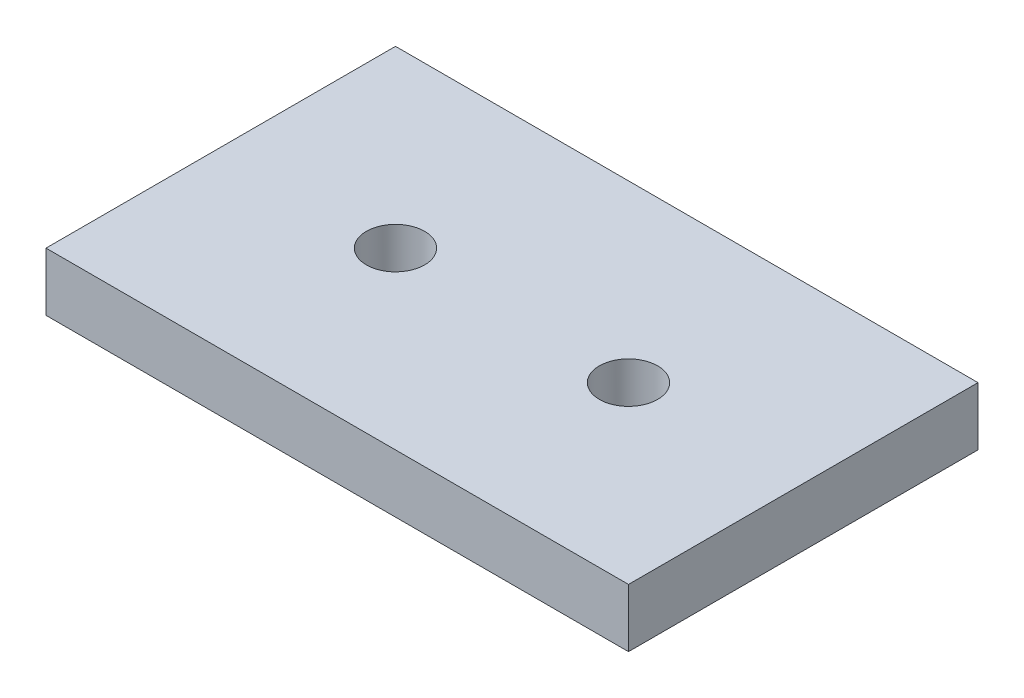
SolidWorks part; units mm, degrees
ref_plane "前视基准面" through (0, 0, 0) normal (0, 0, 1) x (1, 0, 0)
ref_plane "上视基准面" through (0, 0, 0) normal (0, 1, 0) x (1, 0, 0)
ref_plane "右视基准面" through (0, 0, 0) normal (1, 0, 0) x (0, 0, -1)
other "Configuration Table"
sketch "草图1" plane through (0, 0, 0) normal (0, 1, 0) x (1, 0, 0)
  line L1 (-50, -30) -> (50, -30)
  line L2 (-50, -30) -> (-50, 30)
  line L3 (-50, 30) -> (50, 30)
  line L4 (50, -30) -> (50, 30)
  line L5 (0, 30) -> (0, -30) construction
  line L6 (-50, 0) -> (50, 0) construction
  point P0 (0, 0)
extrude "凸台-拉伸1" add sketch "草图1" along normal blind 10
sketch "草图2" plane through (0, 0, 0) normal (0, 1, 0) x (1, 0, 0)
  circle A0 centre (-20, 0) radius 5
extrude "切除-拉伸1" cut sketch "草图2" along normal blind 20
sketch "草图3" plane through (0, 0, 0) normal (0, 1, 0) x (1, 0, 0)
  circle A0 centre (20, 0) radius 5
extrude "切除-拉伸2" cut sketch "草图3" along normal blind 20
sketch "草图4" plane through (0, 0, 0) normal (0, 1, 0) x (1, 0, 0)
  line L0 (-10, -20) -> (10, -20)
